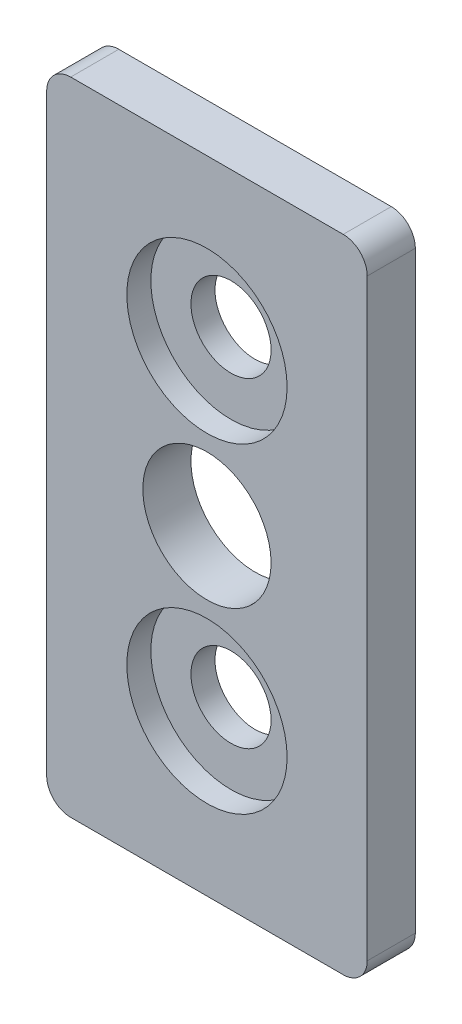
SolidWorks part; units mm, degrees
material "6061-T6 (SS)"
ref_plane "Front Plane" through (0, 0, 0) normal (0, 0, 1) x (1, 0, 0)
ref_plane "Top Plane" through (0, 0, 0) normal (0, 1, 0) x (1, 0, 0)
ref_plane "Right Plane" through (0, 0, 0) normal (1, 0, 0) x (0, 0, -1)
sketch "Sketch1" plane through (0, 0, 0) normal (0, 0, 1) x (1, 0, 0)
  line L0 (10, 20) -> (-10, 0) construction
  line L1 (10, -20) -> (-10, -20)
  line L2 (10, -20) -> (10, 20)
  line L3 (10, 20) -> (-10, 20)
  line L4 (-10, -20) -> (-10, 20)
  line L5 (-10, 0) -> (10, -20) construction
  line L6 (-10, 20) -> (10, 0) construction
  line L7 (10, 0) -> (-10, -20) construction
  line L8 (-10, 0) -> (10, 0) construction
  circle A0 centre (0, -10) radius 2.5
  circle A1 centre (0, 10) radius 2.5
  circle A2 centre (0, 0) radius 4
  dimension "D2" = 5
  dimension "D4" = 5
  dimension "D5" = 8
  dimension "D1" = 40
  dimension "D3" = 20
extrude "Boss-Extrude1" add sketch "Sketch1" along normal blind 3
sketch "Sketch2" plane through (0, 0, 3) normal (0, 0, 1) x (1, 0, 0)
  line L0 (-10, 0) -> (10, 0) construction
  line L1 (-10, 20) -> (-10, -20) construction
  line L2 (10, -20) -> (10, 20) construction
  circle A0 centre (0, -10) radius 5
  circle A1 centre (0, 10) radius 5
  dimension "D1" = 10
  dimension "D2" = 10
extrude "Cut-Extrude1" cut sketch "Sketch2" against normal blind 1.5
fillet "Fillet1" radius 1.5 4 edges at (10, 20, 1.5) (10, -20, 1.5) (-10, -20, 1.5) (-10, 20, 1.5)
